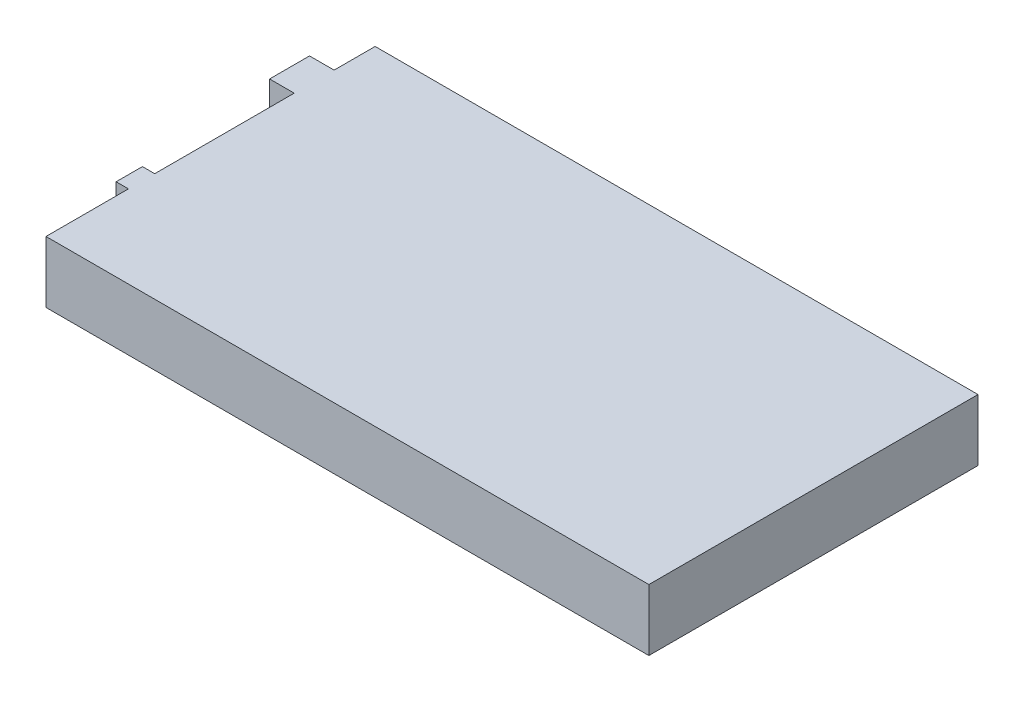
SolidWorks part; units mm, degrees
ref_plane "前视基准面" through (0, 0, 0) normal (0, 0, 1) x (1, 0, 0)
ref_plane "上视基准面" through (0, 0, 0) normal (0, 1, 0) x (1, 0, 0)
ref_plane "右视基准面" through (0, 0, 0) normal (1, 0, 0) x (0, 0, -1)
sketch "草图1" plane through (0, 0, 0) normal (0, 1, 0) x (1, 0, 0)
  line L1 (-49, 26.75) -> (49, 26.75)
  line L2 (-49, 26.75) -> (-49, -26.75)
  line L3 (-49, -26.75) -> (49, -26.75)
  line L4 (49, 26.75) -> (49, -26.75)
  line L5 (-49, 26.75) -> (49, -26.75) construction
  line L6 (-49, -26.75) -> (49, 26.75) construction
  point P0 (0, 0)
  dimension "D1" = 53.5
  dimension "D2" = 98
extrude "凸台-拉伸1" add sketch "草图1" along normal blind 10
sketch "草图2" plane through (0, 10, 0) normal (0, 1, 0) x (1, 0, 0)
  line L0 (49, -26.75) -> (49, 26.75) construction
  line L1 (-42.2385, 20.0854) -> (-53, 20.0854)
  line L2 (-42.2385, 20.0854) -> (-42.2385, 13.5956)
  line L3 (-42.2385, 13.5956) -> (-53, 13.5956)
  line L4 (-53, 20.0854) -> (-53, 13.5956)
  line L5 (-51, -9.0774) -> (-43.6888, -9.0774)
  line L6 (-51, -9.0774) -> (-51, -13.3492)
  line L7 (-51, -13.3492) -> (-43.6888, -13.3492)
  line L8 (-43.6888, -9.0774) -> (-43.6888, -13.3492)
  dimension "D1" = 102
  dimension "D2" = 2
extrude "凸台-拉伸2" add sketch "草图2" against normal up to surface (10 mm away) up to face at (0, 0, 0)
